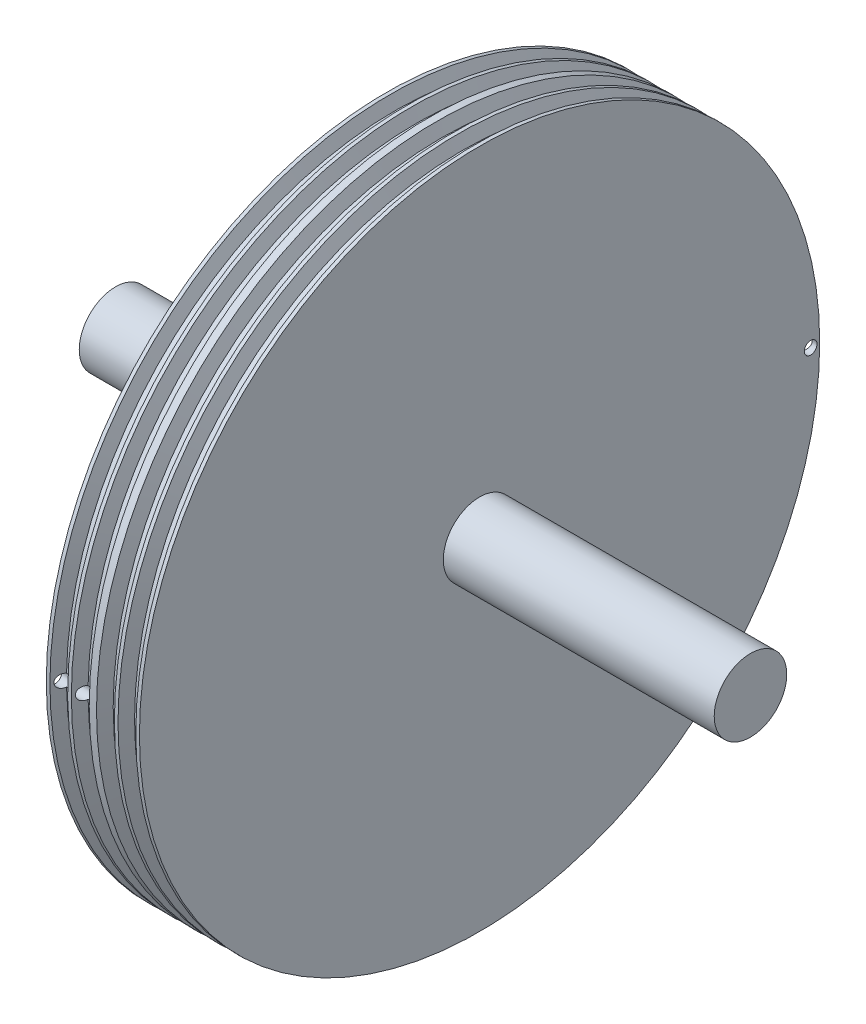
SolidWorks part; units mm, degrees
ref_plane "Front Plane" through (0, 0, 0) normal (0, 0, 1) x (1, 0, 0)
ref_plane "Top Plane" through (0, 0, 0) normal (0, 1, 0) x (1, 0, 0)
ref_plane "Right Plane" through (0, 0, 0) normal (1, 0, 0) x (0, 0, -1)
sketch "Sketch1" plane through (0, 0, 0) normal (0, 0, 1) x (1, 0, 0)
  line L0 (0, 0) -> (70, 0) construction
  line L1 (35, 0) -> (35, 37.5) construction
  line L2 (29.8669, 37.5) -> (29.8669, 4)
  line L7 (29.8669, 4) -> (0, 4)
  line L8 (0, 4) -> (0, 0)
  line L10 (0, 0) -> (70, 0)
  line L11 (70, 0) -> (70, 4)
  line L12 (70, 4) -> (40.1331, 4)
  line L13 (35, 37.5) -> (32.2282, 37.5) construction
  line L14 (35.4, 37.5) -> (34.6, 37.5)
  line L15 (34.6, 37.5) -> (34.0141, 36.2435)
  line L16 (34.0141, 36.2435) -> (33.2141, 36.2435)
  line L17 (33.2141, 36.2435) -> (32.6282, 37.5)
  line L18 (32.6282, 37.5) -> (32.2282, 37.5)
  line L19 (32.2282, 37.5) -> (31.6476, 36.2548)
  line L20 (31.6476, 36.2548) -> (30.8476, 36.2548)
  line L21 (30.8476, 36.2548) -> (30.2669, 37.5)
  line L22 (30.2669, 37.5) -> (29.8669, 37.5)
  line L27 (40.1331, 4) -> (40.1331, 37.5)
  line L29 (39.7331, 37.5) -> (40.1331, 37.5)
  line L30 (39.1524, 36.2548) -> (39.7331, 37.5)
  line L31 (38.3524, 36.2548) -> (39.1524, 36.2548)
  line L32 (37.7718, 37.5) -> (38.3524, 36.2548)
  line L33 (37.3718, 37.5) -> (37.7718, 37.5)
  line L34 (36.7859, 36.2435) -> (37.3718, 37.5)
  line L35 (35.9859, 36.2435) -> (36.7859, 36.2435)
  line L36 (35.4, 37.5) -> (35.9859, 36.2435)
  line L37 (30.2669, 37.5) -> (29.8669, 37.5) construction
  point P7 (0, 0)
  dimension "D1" = 70
  dimension "D2" = 37.5
  dimension "D4" = 4
revolve "Revolve1" add sketch "Sketch1" angle 360 about L10
sketch "Sketch2" plane through (29.8669, 0, 0) normal (-1, 0, 0) x (0, 0, 1)
  line L0 (37.5, 0) -> (36.5, 0) construction
  circle A2 centre (0, 0) radius 37.5 construction
  circle A3 centre (36.5, 0) radius 0.7
sketch "Sketch3" plane through (40.1331, 0, 0) normal (1, 0, 0) x (0, 0, -1)
  line L0 (37.5, 0) -> (36.5, 0) construction
  circle A2 centre (0, 0) radius 37.5 construction
  circle A3 centre (36.5, 0) radius 0.7
extrude "Cut-Extrude1" cut sketch "Sketch3" against normal blind 4
extrude "Cut-Extrude2" cut sketch "Sketch2" against normal blind 4
